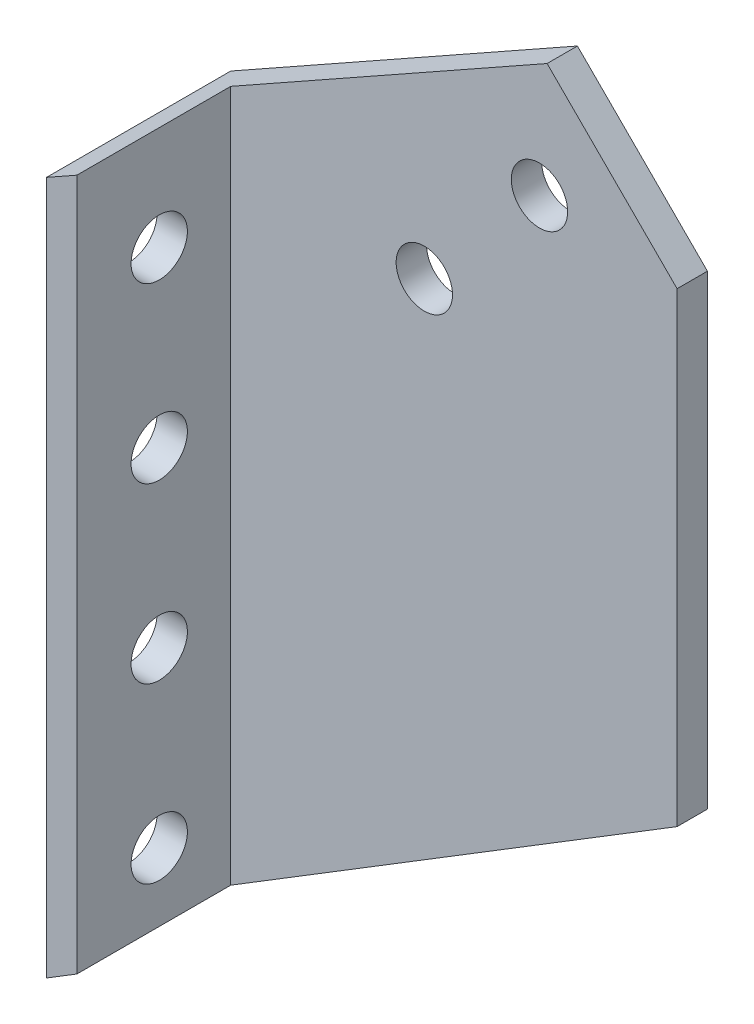
SolidWorks part; units mm, degrees
ref_plane "前视基准面" through (0, 0, 0) normal (0, 0, 1) x (1, 0, 0)
ref_plane "上视基准面" through (0, 0, 0) normal (0, 1, 0) x (1, 0, 0)
ref_plane "右视基准面" through (0, 0, 0) normal (1, 0, 0) x (0, 0, -1)
sketch "草图1" plane through (0, 0, 0) normal (0, 0, 1) x (1, 0, 0)
  line L0 (-1074.6542, -63.3767) -> (48925.3458, -63.3767) construction
  line L1 (-159.1564, -1011.9129) -> (-159.1564, 48988.0871) construction
  line L2 (-119.6564, -63.3767) -> (-119.6564, 256.6233)
  line L3 (-1159.1564, 71.6233) -> (48840.8436, 71.6233) construction
  line L4 (100.3436, 71.6233) -> (100.3436, 286.6233)
  line L5 (40.3436, -1032.1436) -> (40.3436, 48967.8564) construction
  line L6 (-1249.4209, 346.6233) -> (48750.5791, 346.6233) construction
  line L7 (-119.6564, -63.3767) -> (100.3436, 71.6233)
  line L8 (100.3436, 286.6233) -> (40.3436, 346.6233)
  line L9 (40.3436, 346.6233) -> (-119.6564, 256.6233)
  line L10 (1840.8436, -949.9726) -> (1840.8436, 49050.0274) construction
  line L11 (-67.2456, 2321.6233) -> (49932.7544, 2321.6233) construction
  line L12 (1840.8436, 2321.6233) -> (-31377.3484, -35048.8426) construction
  circle A0 centre (-16.3182, 232.3163) radius 13
  circle A1 centre (36.8309, 292.1091) radius 13
  point P21 (-159.1564, 71.6233)
  point P22 (-16.3182, 232.3163)
  point P23 (36.8309, 292.1091)
  dimension "D12" = 26
  dimension "D13" = 26
  dimension "D1" = 320
  dimension "D2" = 39.5
  dimension "D3" = 135
  dimension "D4" = 215
  dimension "D5" = 220
  dimension "D6" = 60
  dimension "D7" = 275
  dimension "D8" = 2000
  dimension "D9" = 2250
  dimension "D10" = 215
  dimension "D11" = 295
extrude "凸台-拉伸1" add sketch "草图1" along normal blind 14
sketch "草图3" plane through (0, 0, 14) normal (0, 0, 1) x (1, 0, 0)
  line L0 (-105.6564, 264.4983) -> (-105.6564, -54.7858)
  line L1 (40.3436, 346.6233) -> (-119.6564, 256.6233) construction
  line L2 (-119.6564, -63.3767) -> (100.3436, 71.6233) construction
  line L3 (-119.6564, 256.6233) -> (-119.6564, -63.3767) construction
  line L9 (-119.6564, -63.3767) -> (100.3436, 71.6233)
  line L10 (100.3436, 71.6233) -> (100.3436, 286.6233)
  line L11 (100.3436, 286.6233) -> (40.3436, 346.6233)
  line L12 (40.3436, 346.6233) -> (-119.6564, 256.6233)
  line L13 (-119.6564, 256.6233) -> (-119.6564, -63.3767)
  line L14 (-119.6564, -63.3767) -> (-105.6564, -54.7858)
  line L17 (-105.6564, 264.4983) -> (-119.6564, 256.6233)
  line L18 (-119.6564, 256.6233) -> (-119.6564, -63.3767)
  dimension "D1" = 14
  dimension "D2" = 0
extrude "凸台-拉伸2" add sketch "草图3" along normal blind 71
sketch "草图5" plane through (-119.6564, 0, 0) normal (-1, 0, 0) x (0, 0, 1)
  line L0 (47, 256.6233) -> (47, -63.3767) construction
  line L1 (85, 256.6233) -> (0, 256.6233) construction
  line L2 (85, -63.3767) -> (0, -63.3767) construction
  line L3 (85, 256.6233) -> (85, -63.3767) construction
  line L4 (0, 216.6233) -> (85, 216.6233) construction
  line L5 (0, 256.6233) -> (0, -63.3767) construction
  circle A0 centre (47, 216.6233) radius 13
  point P12 (47, 216.6233)
  dimension "D1" = 38
  dimension "D2" = 40
extrude "切除-拉伸3" cut sketch "草图5" against normal through all
pattern_linear "阵列(线性)1" count 4 spacing 80 along (0, -1, 0) of "切除-拉伸3"
